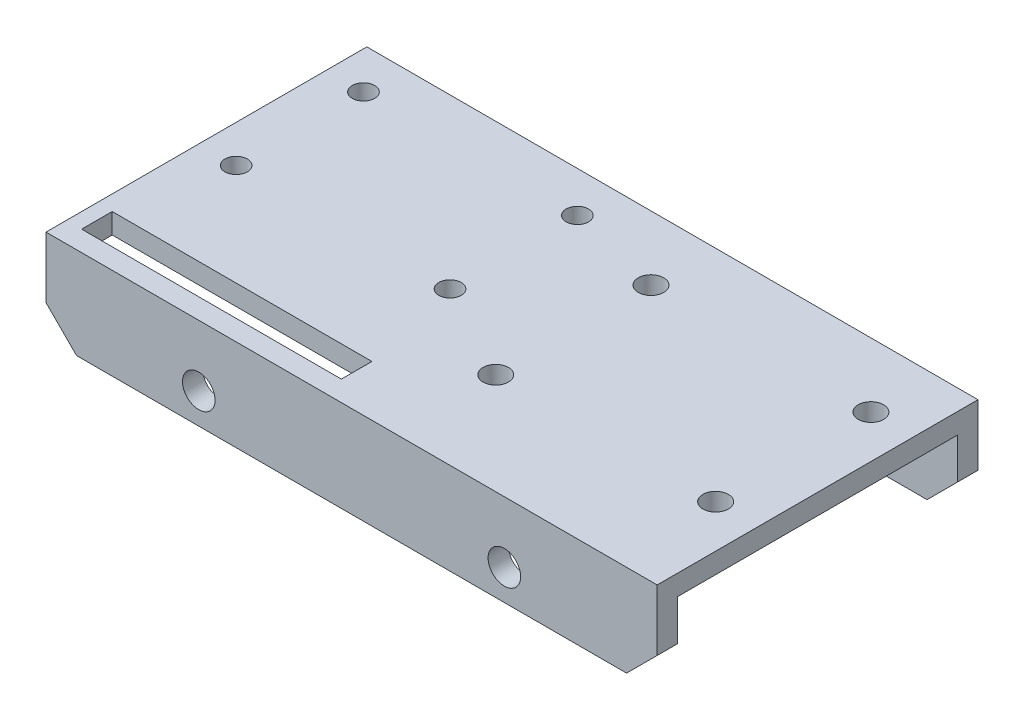
SolidWorks part; units mm, degrees
ref_plane "Front Plane" through (0, 0, 0) normal (0, 0, 1) x (1, 0, 0)
ref_plane "Top Plane" through (0, 0, 0) normal (0, 1, 0) x (1, 0, 0)
ref_plane "Right Plane" through (0, 0, 0) normal (1, 0, 0) x (0, 0, -1)
sketch "Sketch1" plane through (0, 0, 0) normal (0, 1, 0) x (1, 0, 0)
  line L1 (-30, 15.75) -> (30, 15.75)
  line L2 (-30, 15.75) -> (-30, -15.75)
  line L3 (-30, -15.75) -> (30, -15.75)
  line L4 (30, 15.75) -> (30, -15.75)
  line L5 (-30, 15.75) -> (30, -15.75) construction
  line L6 (-30, -15.75) -> (30, 15.75) construction
  point P0 (0, 0)
  dimension "D1" = 31.5
  dimension "D2" = 60
extrude "Boss-Extrude1" add sketch "Sketch1" along normal blind 2
sketch "Sketch2" plane through (0, 0, 0) normal (0, -1, 0) x (1, 0, 0)
  line L0 (-30, -15.75) -> (-30, 15.75) construction
  line L1 (30, -15.75) -> (-30, -15.75)
  line L2 (30, -15.75) -> (30, -13.75)
  line L3 (30, -13.75) -> (-30, -13.75)
  line L4 (-30, -15.75) -> (-30, -13.75)
  line L6 (30, 15.75) -> (-30, 15.75)
  line L7 (30, 15.75) -> (30, 13.75)
  line L8 (30, 13.75) -> (-30, 13.75)
  line L9 (-30, 15.75) -> (-30, 13.75)
  dimension "D1" = 2
  dimension "D2" = 2
extrude "Boss-Extrude2" add sketch "Sketch2" along normal blind 7
sketch "Sketch3" plane through (0, 0, -15.75) normal (0, 0, -1) x (-1, 0, 0)
  line L0 (0, -7) -> (0, 2) construction
  line L1 (30, -7) -> (-30, -7) construction
  line L2 (-30, 2) -> (30, 2) construction
  line L3 (30, -7) -> (0, -7) construction
  line L4 (15, -7) -> (15, 2) construction
  circle A0 centre (15, -4) radius 1.6
  circle A1 centre (-15, -4) radius 1.6
  point P14 (0, 0)
  point P15 (15, -3.7856)
  point P16 (0, 0)
  dimension "D1" = 3.2
  dimension "D2" = 3
extrude "Cut-Extrude1" cut sketch "Sketch3" against normal through all both and the other way through all
chamfer "Chamfer1" distance 3 angle 45 2 edges at (-30, -7, -14.75) (30, -7, -14.75)
chamfer "Chamfer3" distance 3 angle 45 2 edges at (30, -7, 14.75) (-30, -7, 14.75)
sketch "Sketch4" plane through (0, 2, 0) normal (0, 1, 0) x (1, 0, 0)
  circle A0 centre (25.795, -5.801) radius 1.25 construction
  circle A1 centre (4.205, -5.801) radius 1.25 construction
  circle A2 centre (25.795, 9.439) radius 1.25 construction
  circle A3 centre (4.205, 9.439) radius 1.25 construction
  circle A4 centre (-26.335, -0.75) radius 1.1 construction
  circle A5 centre (-26.335, 11.75) radius 1.1 construction
  circle A6 centre (-5.335, -0.75) radius 1.1 construction
  circle A7 centre (-5.335, 11.75) radius 1.1 construction
  circle A8 centre (25.795, -5.801) radius 1.25
  circle A9 centre (4.205, -5.801) radius 1.25
  circle A10 centre (25.795, 9.439) radius 1.25
  circle A11 centre (4.205, 9.439) radius 1.25
  circle A12 centre (-26.335, -0.75) radius 1.1
  circle A13 centre (-26.335, 11.75) radius 1.1
  circle A14 centre (-5.335, -0.75) radius 1.1
  circle A15 centre (-5.335, 11.75) radius 1.1
extrude "Cut-Extrude2" cut sketch "Sketch4" against normal blind 10
sketch "Sketch5" plane through (0, 0, 0) normal (0, -1, 0) x (1, 0, 0)
  line L0 (-30, -13.75) -> (-30, 13.75) construction
  line L1 (-28.5, 13.75) -> (-3, 13.75)
  line L2 (-28.5, 13.75) -> (-28.5, 10.75)
  line L3 (-28.5, 10.75) -> (-3, 10.75)
  line L4 (-3, 13.75) -> (-3, 10.75)
  line L5 (-30, 13.75) -> (30, 13.75) construction
  dimension "D1" = 1.5
  dimension "D2" = 25.5
  dimension "D3" = 3
  dimension "D4" = 0
extrude "Cut-Extrude3" cut sketch "Sketch5" against normal blind 10
equation "\"D2@Sketch2\"=\"D1@Sketch2\""
